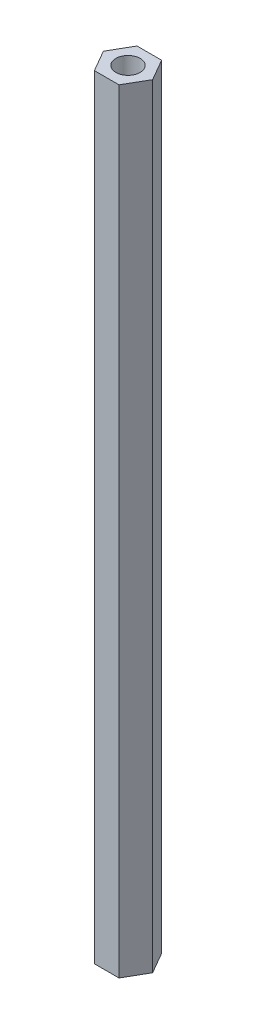
SolidWorks part; units mm, degrees
ref_plane "Front Plane" through (0, 0, 0) normal (0, 0, 1) x (1, 0, 0)
ref_plane "Top Plane" through (0, 0, 0) normal (0, 1, 0) x (1, 0, 0)
ref_plane "Right Plane" through (0, 0, 0) normal (1, 0, 0) x (0, 0, -1)
sketch "Sketch1" plane through (0, 0, 0) normal (0, 1, 0) x (1, 0, 0)
  line L1 (2.0207, 3.5) -> (-2.0207, 3.5)
  line L2 (-2.0207, 3.5) -> (-4.0415, 0)
  line L3 (-4.0415, 0) -> (-2.0207, -3.5)
  line L4 (-2.0207, -3.5) -> (2.0207, -3.5)
  line L5 (2.0207, -3.5) -> (4.0415, 0)
  line L6 (4.0415, 0) -> (2.0207, 3.5)
  circle A0 centre (0, 0) radius 2
  circle A1 centre (0, 0) radius 3.5 construction
  dimension "D1" = 4
  dimension "D2" = 7
extrude "Boss-Extrude1" add sketch "Sketch1" along normal blind 127
